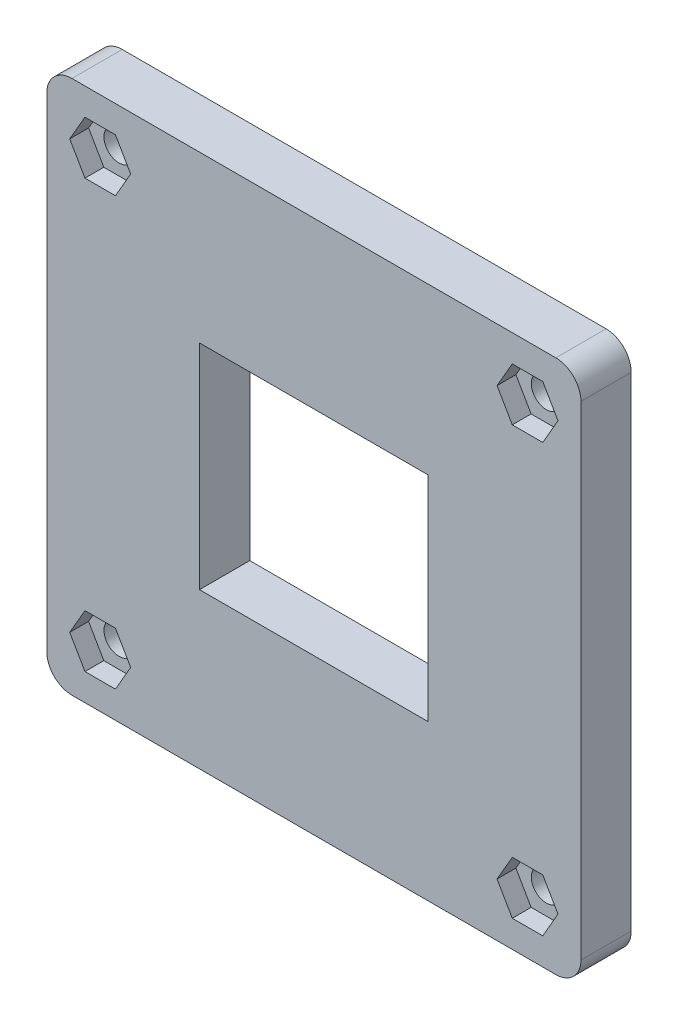
SolidWorks part; units mm, degrees
ref_plane "Front Plane" through (0, 0, 0) normal (0, 0, 1) x (1, 0, 0)
ref_plane "Top Plane" through (0, 0, 0) normal (0, 1, 0) x (1, 0, 0)
ref_plane "Right Plane" through (0, 0, 0) normal (1, 0, 0) x (0, 0, -1)
sketch "Sketch1" plane through (0, 0, 0) normal (0, 0, 1) x (1, 0, 0)
  line L4 (21.25, -19.25) -> (21.25, 19.25)
  line L5 (19.25, 21.25) -> (-19.25, 21.25)
  line L6 (-21.25, 19.25) -> (-21.25, -19.25)
  line L7 (-19.25, -21.25) -> (19.25, -21.25)
  line L8 (21.25, -19.25) -> (21.25, 19.25)
  line L9 (19.25, 21.25) -> (-19.25, 21.25)
  line L10 (-21.25, 19.25) -> (-21.25, -19.25)
  line L11 (-19.25, -21.25) -> (19.25, -21.25)
  line L21 (-8.9, -8.7) -> (8.9, -8.7) construction
  line L22 (-8.9, 7.9) -> (-8.9, -8.7) construction
  line L23 (8.9, 7.9) -> (-8.9, 7.9) construction
  line L24 (8.9, -8.7) -> (8.9, 7.9) construction
  line L25 (-8.9, -8.7) -> (8.9, -8.7) construction
  line L26 (-8.9, 7.9) -> (-8.9, -8.7) construction
  line L27 (8.9, 7.9) -> (-8.9, 7.9) construction
  line L28 (8.9, -8.7) -> (8.9, 7.9) construction
  line L29 (-9.1, -8.9) -> (9.1, -8.9)
  line L30 (9.1, -8.9) -> (9.1, 8.1)
  line L31 (9.1, 8.1) -> (-9.1, 8.1)
  line L32 (-9.1, 8.1) -> (-9.1, -8.9)
  circle A0 centre (-17, -17) radius 1.2 construction
  circle A1 centre (17, -17) radius 1.2 construction
  circle A2 centre (17, 17) radius 1.2 construction
  circle A3 centre (-17, 17) radius 1.2 construction
  arc A4 (21.25, 19.25) -> (19.25, 21.25) centre (19.25, 19.25) ccw
  arc A5 (-19.25, 21.25) -> (-21.25, 19.25) centre (-19.25, 19.25) ccw
  arc A6 (-21.25, -19.25) -> (-19.25, -21.25) centre (-19.25, -19.25) ccw
  arc A7 (19.25, -21.25) -> (21.25, -19.25) centre (19.25, -19.25) ccw
  arc A8 (21.25, 19.25) -> (19.25, 21.25) centre (19.25, 19.25) ccw
  arc A9 (-19.25, 21.25) -> (-21.25, 19.25) centre (-19.25, 19.25) ccw
  arc A10 (-21.25, -19.25) -> (-19.25, -21.25) centre (-19.25, -19.25) ccw
  arc A11 (19.25, -21.25) -> (21.25, -19.25) centre (19.25, -19.25) ccw
  circle A12 centre (-17, -17) radius 1.2
  circle A13 centre (17, -17) radius 1.2
  circle A14 centre (17, 17) radius 1.2
  circle A15 centre (-17, 17) radius 1.2
  dimension "D3" = 0.2
  dimension "D1" = 0
extrude "Boss-Extrude1" add sketch "Sketch1" along normal blind 4
sketch "Sketch2" plane through (0, 0, 0) normal (0, 0, -1) x (-1, 0, 0)
  line L0 (-9.5, 17) -> (9.5, 17) construction
  line L1 (-9.5, 18.25) -> (9.5, 18.25)
  line L2 (-9.5, 15.75) -> (9.5, 15.75)
  line L3 (-9.5, 16) -> (-9.5, 18) construction
  line L4 (9.5, 18) -> (9.5, 16) construction
  arc A0 (-9.5, 18.25) -> (-9.5, 15.75) centre (-9.5, 17) ccw
  arc A1 (9.5, 15.75) -> (9.5, 18.25) centre (9.5, 17) ccw
  point P2 (0, 17)
  point P7 (-17, 17)
  dimension "D1" = 2.5
extrude "Cut-Extrude3" cut sketch "Sketch2" against normal blind 1
sketch "Sketch3" plane through (0, 0, 4) normal (0, 0, 1) x (1, 0, 0)
  line L0 (-18.2124, -14.9) -> (-19.4249, -17)
  line L1 (15.7876, -14.9) -> (14.5751, -17)
  line L2 (14.5751, -17) -> (15.7876, -19.1)
  line L3 (15.7876, -19.1) -> (18.2124, -19.1)
  line L4 (18.2124, -19.1) -> (19.4249, -17)
  line L5 (19.4249, -17) -> (18.2124, -14.9)
  line L6 (18.2124, -14.9) -> (15.7876, -14.9)
  line L7 (-19.4249, -17) -> (-18.2124, -19.1)
  line L8 (-18.2124, -19.1) -> (-15.7876, -19.1)
  line L9 (-15.7876, -19.1) -> (-14.5751, -17)
  line L10 (-14.5751, -17) -> (-15.7876, -14.9)
  line L11 (-15.7876, -14.9) -> (-18.2124, -14.9)
  line L12 (-18.2124, 19.1) -> (-19.4249, 17)
  line L13 (-19.4249, 17) -> (-18.2124, 14.9)
  line L14 (-18.2124, 14.9) -> (-15.7876, 14.9)
  line L15 (-15.7876, 14.9) -> (-14.5751, 17)
  line L16 (-14.5751, 17) -> (-15.7876, 19.1)
  line L17 (-15.7876, 19.1) -> (-18.2124, 19.1)
  line L18 (15.7876, 19.1) -> (14.5751, 17)
  line L19 (14.5751, 17) -> (15.7876, 14.9)
  line L20 (15.7876, 14.9) -> (18.2124, 14.9)
  line L21 (18.2124, 14.9) -> (19.4249, 17)
  line L22 (19.4249, 17) -> (18.2124, 19.1)
  line L23 (18.2124, 19.1) -> (15.7876, 19.1)
  line L24 (15.7876, -14.9) -> (-18.2124, -14.9) construction
  line L25 (15.7876, -14.9) -> (15.7876, 19.1) construction
  circle A0 centre (17, -17) radius 2.1 construction
  circle A1 centre (-17, -17) radius 2.1 construction
  circle A2 centre (-17, 17) radius 2.1 construction
  circle A3 centre (17, 17) radius 2.1 construction
  dimension "D1" = 4.2
  dimension "D2" = 2
  dimension "D4" = 90
  dimension "D3" = 2
extrude "Cut-Extrude4" cut sketch "Sketch3" against normal blind 1.5
